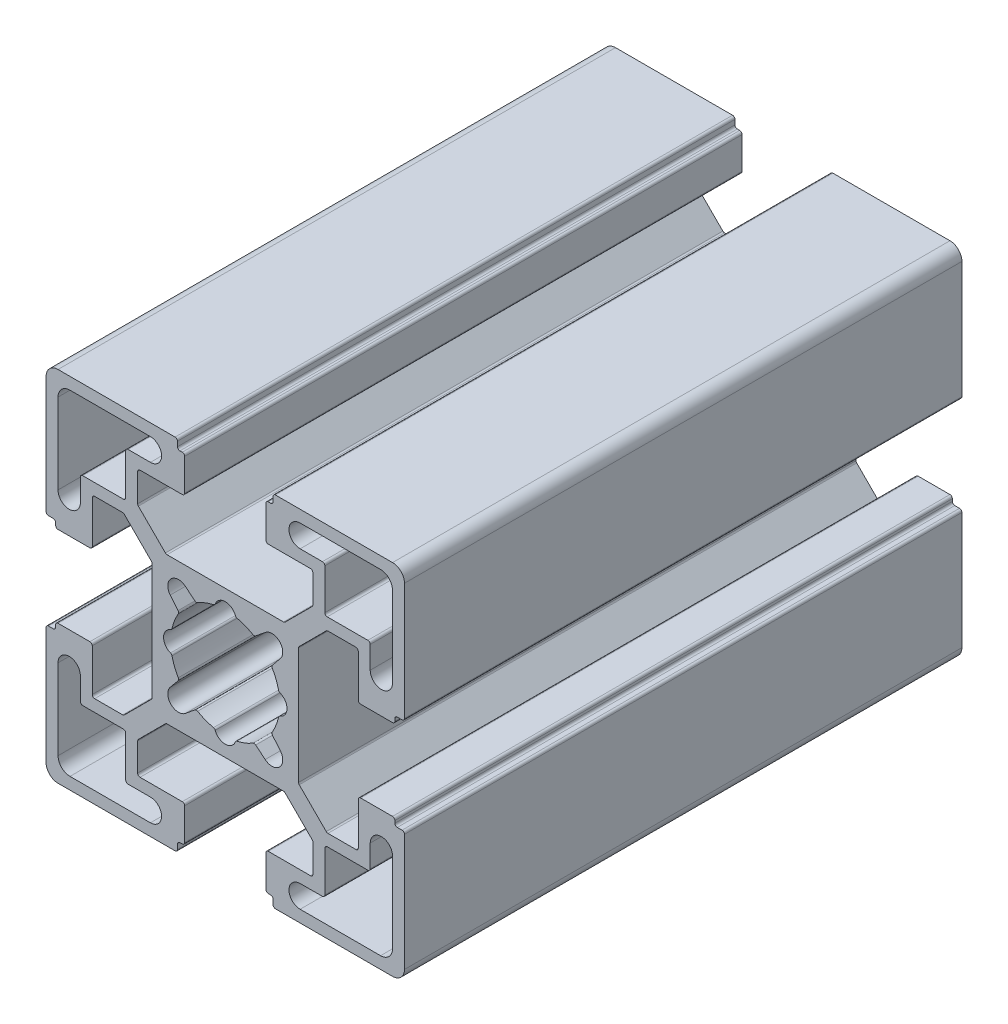
SolidWorks part; units mm, degrees
material "6063-T5"
ref_plane "Plane1" through (0, 0, 0) normal (0, 0, 1) x (1, 0, 0)
ref_plane "Plane2" through (0, 0, 0) normal (0, 1, 0) x (1, 0, 0)
ref_plane "Plane3" through (0, 0, 0) normal (1, 0, 0) x (0, 0, -1)
sketch "Sketch1" plane through (0, 0, 0) normal (0, 0, 1) x (1, 0, 0)
  line L0 (-3.8182, 5.9298) -> (-5.0112, 6.9114)
  line L1 (-6.9114, 5.0112) -> (-5.9298, 3.8182)
  line L2 (-5.9298, -3.8182) -> (-6.9114, -5.0112)
  line L3 (-5.0112, -6.9114) -> (-3.8182, -5.9298)
  line L4 (3.8182, -5.9298) -> (5.0112, -6.9114)
  line L5 (6.9114, -5.0112) -> (5.9298, -3.8182)
  line L6 (5.9298, 3.8182) -> (6.9114, 5.0112)
  line L7 (5.0112, 6.9114) -> (3.8182, 5.9298)
  line L8 (-19.5, -21) -> (-9.4, -21)
  line L9 (-9.4, -18.2) -> (-12.2, -18.2)
  line L10 (-12.5, -17.9) -> (-12.5, -12.8)
  line L11 (-12.8, -12.5) -> (-17.9, -12.5)
  line L12 (-18.2, -12.2) -> (-18.2, -9.4)
  line L13 (-21, -9.4) -> (-21, -19.5)
  line L14 (17.9, -12.5) -> (12.8, -12.5)
  line L15 (12.5, -12.8) -> (12.5, -17.9)
  line L16 (12.2, -18.2) -> (9.4, -18.2)
  line L17 (9.4, -21) -> (19.5, -21)
  line L18 (21, -19.5) -> (21, -9.4)
  line L19 (18.2, -9.4) -> (18.2, -12.2)
  line L20 (19.5, 21) -> (9.4, 21)
  line L21 (9.4, 18.2) -> (12.2, 18.2)
  line L22 (12.5, 17.9) -> (12.5, 12.8)
  line L23 (12.8, 12.5) -> (17.9, 12.5)
  line L24 (18.2, 12.2) -> (18.2, 9.4)
  line L25 (21, 9.4) -> (21, 19.5)
  line L26 (-18.2, 9.4) -> (-18.2, 12.2)
  line L27 (-17.9, 12.5) -> (-12.8, 12.5)
  line L28 (-12.5, 12.8) -> (-12.5, 17.9)
  line L29 (-12.2, 18.2) -> (-9.4, 18.2)
  line L30 (-9.4, 21) -> (-19.5, 21)
  line L31 (-21, 19.5) -> (-21, 9.4)
  line L32 (22.5, 6.3) -> (22.5, 21)
  line L33 (21.6, 6) -> (22.2, 6)
  line L34 (21.3, 5.4) -> (21.3, 5.7)
  line L36 (16.7, 10.7) -> (16.7, 5.4)
  line L37 (12.892, 11) -> (16.4, 11)
  line L38 (9.2879, 7.5201) -> (12.6799, 10.9121)
  line L39 (9.2, -7.308) -> (9.2, 7.308)
  line L40 (12.6799, -10.9121) -> (9.2879, -7.5201)
  line L41 (16.4, -11) -> (12.892, -11)
  line L42 (16.7, -5.4) -> (16.7, -10.7)
  line L44 (21.3, -5.7) -> (21.3, -5.4)
  line L45 (22.2, -6) -> (21.6, -6)
  line L46 (22.5, -21) -> (22.5, -6.3)
  line L47 (6.3, -22.5) -> (21, -22.5)
  line L48 (6, -21.6) -> (6, -22.2)
  line L49 (5.4, -21.3) -> (5.7, -21.3)
  line L51 (10.7, -16.7) -> (5.4, -16.7)
  line L52 (11, -12.892) -> (11, -16.4)
  line L53 (7.5201, -9.2879) -> (10.9121, -12.6799)
  line L54 (-7.4322, -9.2) -> (7.308, -9.2)
  line L55 (-10.9121, -12.6799) -> (-7.4322, -9.2)
  line L56 (-11, -16.4) -> (-11, -12.892)
  line L57 (-5.4, -16.7) -> (-10.7, -16.7)
  line L59 (-5.7, -21.3) -> (-5.4, -21.3)
  line L60 (-6, -22.2) -> (-6, -21.6)
  line L61 (-21, -22.5) -> (-6.3, -22.5)
  line L62 (-22.5, -6.3) -> (-22.5, -21)
  line L63 (-21.6, -6) -> (-22.2, -6)
  line L64 (-21.3, -5.4) -> (-21.3, -5.7)
  line L66 (-16.7, -10.7) -> (-16.7, -5.4)
  line L67 (-12.892, -11) -> (-16.4, -11)
  line L68 (-9.2879, -7.5201) -> (-12.6799, -10.9121)
  line L69 (-9.2, 7.308) -> (-9.2, -7.308)
  line L70 (-12.6799, 10.9121) -> (-9.2879, 7.5201)
  line L71 (-16.4, 11) -> (-12.892, 11)
  line L72 (-16.7, 5.4) -> (-16.7, 10.7)
  line L74 (-21.3, 5.7) -> (-21.3, 5.4)
  line L75 (-22.2, 6) -> (-21.6, 6)
  line L76 (-22.5, 21) -> (-22.5, 6.3)
  line L77 (-6.3, 22.5) -> (-21, 22.5)
  line L78 (-6, 21.6) -> (-6, 22.2)
  line L79 (-5.4, 21.3) -> (-5.7, 21.3)
  line L81 (-10.7, 16.7) -> (-5.4, 16.7)
  line L82 (-11, 12.892) -> (-11, 16.4)
  line L83 (-7.5201, 9.2879) -> (-10.9121, 12.6799)
  line L84 (7.308, 9.2) -> (-7.308, 9.2)
  line L85 (10.9121, 12.6799) -> (7.5201, 9.2879)
  line L86 (11, 16.4) -> (11, 12.892)
  line L87 (5.4, 16.7) -> (10.7, 16.7)
  line L89 (5.7, 21.3) -> (5.4, 21.3)
  line L90 (6, 22.2) -> (6, 21.6)
  line L91 (21, 22.5) -> (6.3, 22.5)
  line L92 (-5.1, 17) -> (-5.1, 21)
  line L93 (-21, 5.1) -> (-17, 5.1)
  line L94 (-17, -5.1) -> (-21, -5.1)
  line L95 (-5.1, -21) -> (-5.1, -17)
  line L96 (5.1, -17) -> (5.1, -21)
  line L97 (21, -5.1) -> (17, -5.1)
  line L98 (17, 5.1) -> (21, 5.1)
  line L99 (5.1, 21) -> (5.1, 17)
  arc A0 (-1.4794, 6.6883) -> (-1.2635, 6.8756) centre (-1.5442, 6.9813) ccw
  arc A1 (-1.4794, 6.6883) -> (-3.4754, 5.9029) centre (0, 0) ccw
  arc A2 (-3.8182, 5.9298) -> (-3.4754, 5.9029) centre (-3.6276, 6.1614) ccw
  arc A3 (-5.0112, 6.9114) -> (-6.9114, 5.0112) centre (-5.869, 5.869) ccw
  arc A4 (-5.9029, 3.4754) -> (-5.9298, 3.8182) centre (-6.1614, 3.6276) ccw
  arc A5 (-5.9029, 3.4754) -> (-6.6883, 1.4794) centre (0, 0) ccw
  arc A6 (-6.8756, 1.2635) -> (-6.6883, 1.4794) centre (-6.9813, 1.5442) ccw
  arc A7 (-6.8756, 1.2635) -> (-6.8756, -1.2635) centre (-6.4, 0) ccw
  arc A8 (-6.6883, -1.4794) -> (-6.8756, -1.2635) centre (-6.9813, -1.5442) ccw
  arc A9 (-6.6883, -1.4794) -> (-5.9029, -3.4754) centre (0, 0) ccw
  arc A10 (-5.9298, -3.8182) -> (-5.9029, -3.4754) centre (-6.1614, -3.6276) ccw
  arc A11 (-6.9114, -5.0112) -> (-5.0112, -6.9114) centre (-5.869, -5.869) ccw
  arc A12 (-3.4754, -5.9029) -> (-3.8182, -5.9298) centre (-3.6276, -6.1614) ccw
  arc A13 (-3.4754, -5.9029) -> (-1.4794, -6.6883) centre (0, 0) ccw
  arc A14 (-1.2635, -6.8756) -> (-1.4794, -6.6883) centre (-1.5442, -6.9812) ccw
  arc A15 (-1.2635, -6.8756) -> (1.2635, -6.8756) centre (0, -6.4) ccw
  arc A16 (1.4794, -6.6883) -> (1.2635, -6.8756) centre (1.5442, -6.9812) ccw
  arc A17 (1.4794, -6.6883) -> (3.4754, -5.9029) centre (0, 0) ccw
  arc A18 (3.8182, -5.9298) -> (3.4754, -5.9029) centre (3.6276, -6.1614) ccw
  arc A19 (5.0112, -6.9114) -> (6.9114, -5.0112) centre (5.869, -5.869) ccw
  arc A20 (5.9029, -3.4754) -> (5.9298, -3.8182) centre (6.1614, -3.6276) ccw
  arc A21 (5.9029, -3.4754) -> (6.6883, -1.4794) centre (0, 0) ccw
  arc A22 (6.8756, -1.2635) -> (6.6883, -1.4794) centre (6.9812, -1.5442) ccw
  arc A23 (6.8756, -1.2635) -> (6.8756, 1.2635) centre (6.4, 0) ccw
  arc A24 (6.6883, 1.4794) -> (6.8756, 1.2635) centre (6.9812, 1.5442) ccw
  arc A25 (6.6883, 1.4794) -> (5.9029, 3.4754) centre (0, 0) ccw
  arc A26 (5.9298, 3.8182) -> (5.9029, 3.4754) centre (6.1614, 3.6276) ccw
  arc A27 (6.9114, 5.0112) -> (5.0112, 6.9114) centre (5.869, 5.869) ccw
  arc A28 (3.4754, 5.9029) -> (3.8182, 5.9298) centre (3.6276, 6.1614) ccw
  arc A29 (3.4754, 5.9029) -> (1.4794, 6.6883) centre (0, 0) ccw
  arc A30 (1.2635, 6.8756) -> (1.4794, 6.6883) centre (1.5442, 6.9813) ccw
  arc A31 (1.2635, 6.8756) -> (-1.2635, 6.8756) centre (0, 6.4) ccw
  arc A32 (-21, -19.5) -> (-19.5, -21) centre (-19.5, -19.5) ccw
  arc A33 (-9.4, -21) -> (-9.4, -18.2) centre (-9.4, -19.6) ccw
  arc A34 (-12.5, -17.9) -> (-12.2, -18.2) centre (-12.2, -17.9) ccw
  arc A35 (-12.5, -12.8) -> (-12.8, -12.5) centre (-12.8, -12.8) ccw
  arc A36 (-18.2, -12.2) -> (-17.9, -12.5) centre (-17.9, -12.2) ccw
  arc A37 (-18.2, -9.4) -> (-21, -9.4) centre (-19.6, -9.4) ccw
  arc A38 (17.9, -12.5) -> (18.2, -12.2) centre (17.9, -12.2) ccw
  arc A39 (12.8, -12.5) -> (12.5, -12.8) centre (12.8, -12.8) ccw
  arc A40 (12.2, -18.2) -> (12.5, -17.9) centre (12.2, -17.9) ccw
  arc A41 (9.4, -18.2) -> (9.4, -21) centre (9.4, -19.6) ccw
  arc A42 (19.5, -21) -> (21, -19.5) centre (19.5, -19.5) ccw
  arc A43 (21, -9.4) -> (18.2, -9.4) centre (19.6, -9.4) ccw
  arc A44 (21, 19.5) -> (19.5, 21) centre (19.5, 19.5) ccw
  arc A45 (9.4, 21) -> (9.4, 18.2) centre (9.4, 19.6) ccw
  arc A46 (12.5, 17.9) -> (12.2, 18.2) centre (12.2, 17.9) ccw
  arc A47 (12.5, 12.8) -> (12.8, 12.5) centre (12.8, 12.8) ccw
  arc A48 (18.2, 12.2) -> (17.9, 12.5) centre (17.9, 12.2) ccw
  arc A49 (18.2, 9.4) -> (21, 9.4) centre (19.6, 9.4) ccw
  arc A50 (-21, 9.4) -> (-18.2, 9.4) centre (-19.6, 9.4) ccw
  arc A51 (-17.9, 12.5) -> (-18.2, 12.2) centre (-17.9, 12.2) ccw
  arc A52 (-12.8, 12.5) -> (-12.5, 12.8) centre (-12.8, 12.8) ccw
  arc A53 (-12.2, 18.2) -> (-12.5, 17.9) centre (-12.2, 17.9) ccw
  arc A54 (-9.4, 18.2) -> (-9.4, 21) centre (-9.4, 19.6) ccw
  arc A55 (-19.5, 21) -> (-21, 19.5) centre (-19.5, 19.5) ccw
  arc A56 (22.2, 6) -> (22.5, 6.3) centre (22.2, 6.3) ccw
  arc A57 (21.6, 6) -> (21.3, 5.7) centre (21.6, 5.7) ccw
  arc A58 (-17, -5.1) -> (-16.7, -5.4) centre (-17, -5.4) cw
  arc A59 (16.7, 10.7) -> (16.4, 11) centre (16.4, 10.7) ccw
  arc A60 (12.892, 11) -> (12.6799, 10.9121) centre (12.892, 10.7) ccw
  arc A61 (9.2879, 7.5201) -> (9.2, 7.308) centre (9.5, 7.308) ccw
  arc A62 (9.2, -7.308) -> (9.2879, -7.5201) centre (9.5, -7.308) ccw
  arc A63 (12.6799, -10.9121) -> (12.892, -11) centre (12.892, -10.7) ccw
  arc A64 (16.4, -11) -> (16.7, -10.7) centre (16.4, -10.7) ccw
  arc A65 (-17, 5.1) -> (-16.7, 5.4) centre (-17, 5.4) ccw
  arc A66 (21.3, -5.7) -> (21.6, -6) centre (21.6, -5.7) ccw
  arc A67 (22.5, -6.3) -> (22.2, -6) centre (22.2, -6.3) ccw
  arc A68 (21, -22.5) -> (22.5, -21) centre (21, -21) ccw
  arc A69 (6, -22.2) -> (6.3, -22.5) centre (6.3, -22.2) ccw
  arc A70 (6, -21.6) -> (5.7, -21.3) centre (5.7, -21.6) ccw
  arc A71 (-5.1, 17) -> (-5.4, 16.7) centre (-5.4, 17) cw
  arc A72 (10.7, -16.7) -> (11, -16.4) centre (10.7, -16.4) ccw
  arc A73 (11, -12.892) -> (10.9121, -12.6799) centre (10.7, -12.892) ccw
  arc A74 (7.5201, -9.2879) -> (7.308, -9.2) centre (7.308, -9.5) ccw
  arc A75 (-10.9121, -12.6799) -> (-11, -12.892) centre (-10.7, -12.892) ccw
  arc A76 (-11, -16.4) -> (-10.7, -16.7) centre (-10.7, -16.4) ccw
  arc A77 (5.1, 17) -> (5.4, 16.7) centre (5.4, 17) ccw
  arc A78 (-5.7, -21.3) -> (-6, -21.6) centre (-5.7, -21.6) ccw
  arc A79 (-6.3, -22.5) -> (-6, -22.2) centre (-6.3, -22.2) ccw
  arc A80 (-22.5, -21) -> (-21, -22.5) centre (-21, -21) ccw
  arc A81 (-22.2, -6) -> (-22.5, -6.3) centre (-22.2, -6.3) ccw
  arc A82 (-21.6, -6) -> (-21.3, -5.7) centre (-21.6, -5.7) ccw
  arc A83 (16.7, 5.4) -> (17, 5.1) centre (17, 5.4) ccw
  arc A84 (-16.7, -10.7) -> (-16.4, -11) centre (-16.4, -10.7) ccw
  arc A85 (-12.892, -11) -> (-12.6799, -10.9121) centre (-12.892, -10.7) ccw
  arc A86 (-9.2879, -7.5201) -> (-9.2, -7.308) centre (-9.5, -7.308) ccw
  arc A87 (-9.2, 7.308) -> (-9.2879, 7.5201) centre (-9.5, 7.308) ccw
  arc A88 (-12.6799, 10.9121) -> (-12.892, 11) centre (-12.892, 10.7) ccw
  arc A89 (-16.4, 11) -> (-16.7, 10.7) centre (-16.4, 10.7) ccw
  arc A90 (17, -5.1) -> (16.7, -5.4) centre (17, -5.4) ccw
  arc A91 (-21.3, 5.7) -> (-21.6, 6) centre (-21.6, 5.7) ccw
  arc A92 (-22.5, 6.3) -> (-22.2, 6) centre (-22.2, 6.3) ccw
  arc A93 (-21, 22.5) -> (-22.5, 21) centre (-21, 21) ccw
  arc A94 (-6, 22.2) -> (-6.3, 22.5) centre (-6.3, 22.2) ccw
  arc A95 (-6, 21.6) -> (-5.7, 21.3) centre (-5.7, 21.6) ccw
  arc A96 (5.1, -17) -> (5.4, -16.7) centre (5.4, -17) cw
  arc A97 (-10.7, 16.7) -> (-11, 16.4) centre (-10.7, 16.4) ccw
  arc A98 (-11, 12.892) -> (-10.9121, 12.6799) centre (-10.7, 12.892) ccw
  arc A99 (-7.5201, 9.2879) -> (-7.308, 9.2) centre (-7.308, 9.5) ccw
  arc A100 (7.308, 9.2) -> (7.5201, 9.2879) centre (7.308, 9.5) ccw
  arc A101 (10.9121, 12.6799) -> (11, 12.892) centre (10.7, 12.892) ccw
  arc A102 (11, 16.4) -> (10.7, 16.7) centre (10.7, 16.4) ccw
  arc A103 (-5.1, -17) -> (-5.4, -16.7) centre (-5.4, -17) ccw
  arc A104 (5.7, 21.3) -> (6, 21.6) centre (5.7, 21.6) ccw
  arc A105 (6.3, 22.5) -> (6, 22.2) centre (6.3, 22.2) ccw
  arc A106 (22.5, 21) -> (21, 22.5) centre (21, 21) ccw
  arc A107 (-21, 5.1) -> (-21.3, 5.4) centre (-21, 5.4) cw
  arc A108 (-21, -5.1) -> (-21.3, -5.4) centre (-21, -5.4) ccw
  arc A109 (-5.1, -21) -> (-5.4, -21.3) centre (-5.4, -21) cw
  arc A110 (5.1, -21) -> (5.4, -21.3) centre (5.4, -21) ccw
  arc A111 (21, -5.1) -> (21.3, -5.4) centre (21, -5.4) cw
  arc A112 (21, 5.1) -> (21.3, 5.4) centre (21, 5.4) ccw
  arc A113 (5.1, 21) -> (5.4, 21.3) centre (5.4, 21) cw
  arc A114 (-5.1, 21) -> (-5.4, 21.3) centre (-5.4, 21) ccw
  point P299 (0, 22.5)
  point P300 (22.5, 22.5)
  point P301 (-22.5, 22.5)
  point P302 (-22.5, 0)
  point P303 (-22.5, -22.5)
  point P304 (0, -22.5)
  point P305 (22.5, -22.5)
  point P306 (22.5, 0)
  point P308 (0, 0)
extrude "Ressalto-extrusão2" add sketch "Sketch1" along normal blind 70 contours L32 A106 L91 A105 L90 A104 L89 L99 A77 L87 A102 L86 A101 L85 A100 L84 A99 L83 A98 L82 A97 L81 A71 L92 L79 A95 L78 A94 L77 A93 L76 A92 L75 A91 L74 L93 A65 L72 A89 L71 A88 L70 A87 L69 A86 L68 A85 L67 A84 L66 A58
